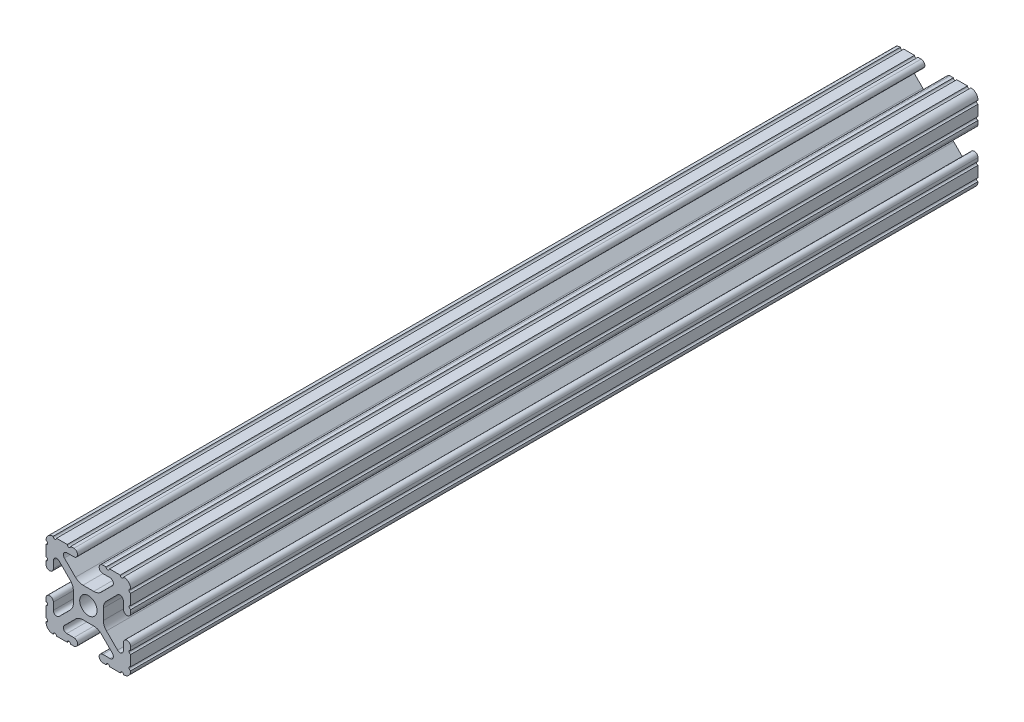
SolidWorks part; units mm, degrees
material "6061 Alloy"
ref_plane "Front Plane" through (0, 0, 0) normal (0, 0, 1) x (1, 0, 0)
ref_plane "Top Plane" through (0, 0, 0) normal (0, 1, 0) x (1, 0, 0)
ref_plane "Right Plane" through (0, 0, 0) normal (1, 0, 0) x (0, 0, -1)
ref_plane "Plane1" through (0, 0, -25.4) normal (0, 0, -1) x (-1, 0, 0)
sketch "Sketch1" plane through (0, 0, -25.4) normal (0, 0, -1) x (-1, 0, 0)
  line L0 (12.7, -9.5504) -> (12.7, -6.3331)
  line L1 (12.7, -5.3171) -> (12.7, -4.3434)
  line L2 (10.4902, -4.3434) -> (10.4902, -6.4748)
  line L3 (8.7558, -7.1932) -> (5.4257, -3.8632)
  line L4 (4.4958, -1.6181) -> (4.4958, 1.6181)
  line L5 (5.4257, 3.8632) -> (8.7558, 7.1932)
  line L6 (10.4902, 6.4748) -> (10.4902, 4.3434)
  line L7 (12.7, 4.3434) -> (12.7, 5.3171)
  line L8 (12.7, 6.3331) -> (12.7, 9.5504)
  line L9 (9.5504, 12.7) -> (6.3331, 12.7)
  line L10 (5.3171, 12.7) -> (4.3434, 12.7)
  line L11 (4.3434, 10.4902) -> (6.4748, 10.4902)
  line L12 (7.1932, 8.7558) -> (3.8632, 5.4257)
  line L13 (1.6181, 4.4958) -> (-1.6181, 4.4958)
  line L14 (-3.8632, 5.4257) -> (-7.1932, 8.7558)
  line L15 (-6.4748, 10.4902) -> (-4.3434, 10.4902)
  line L16 (-4.3434, 12.7) -> (-5.3171, 12.7)
  line L17 (-6.3331, 12.7) -> (-9.5504, 12.7)
  line L18 (-12.7, 9.5504) -> (-12.7, 6.3331)
  line L19 (-12.7, 5.3171) -> (-12.7, 4.3434)
  line L20 (-10.4902, 4.3434) -> (-10.4902, 6.4748)
  line L21 (-8.7558, 7.1932) -> (-5.4257, 3.8632)
  line L22 (-4.4958, 1.6181) -> (-4.4958, -1.6181)
  line L23 (-5.4257, -3.8632) -> (-8.7558, -7.1932)
  line L24 (-10.4902, -6.4748) -> (-10.4902, -4.3434)
  line L25 (-12.7, -4.3434) -> (-12.7, -5.3171)
  line L26 (-12.7, -6.3331) -> (-12.7, -9.5504)
  line L27 (-9.5504, -12.7) -> (-6.3331, -12.7)
  line L28 (-5.3171, -12.7) -> (-4.3434, -12.7)
  line L29 (-4.3434, -10.4902) -> (-6.4748, -10.4902)
  line L30 (-7.1932, -8.7558) -> (-3.8632, -5.4257)
  line L31 (-1.6181, -4.4958) -> (1.6181, -4.4958)
  line L32 (3.8632, -5.4257) -> (7.1932, -8.7558)
  line L33 (6.4748, -10.4902) -> (4.3434, -10.4902)
  line L34 (4.3434, -12.7) -> (5.3171, -12.7)
  line L35 (6.3331, -12.7) -> (9.5504, -12.7)
  arc A0 (12.6998, -10.5664) -> (12.7, -9.5504) centre (12.7, -10.0584) cw
  arc A1 (12.7, -6.3331) -> (12.7, -5.3171) centre (12.7, -5.8251) cw
  arc A2 (12.7, -4.3434) -> (10.4902, -4.3434) centre (11.5951, -4.3434) ccw
  arc A3 (10.4902, -6.4748) -> (8.7558, -7.1932) centre (9.4742, -6.4748) cw
  arc A4 (5.4257, -3.8632) -> (4.4958, -1.6181) centre (7.6708, -1.6181) cw
  arc A5 (4.4958, 1.6181) -> (5.4257, 3.8632) centre (7.6708, 1.6181) cw
  arc A6 (8.7558, 7.1932) -> (10.4902, 6.4748) centre (9.4742, 6.4748) cw
  arc A7 (10.4902, 4.3434) -> (12.7, 4.3434) centre (11.5951, 4.3434) ccw
  arc A8 (12.7, 5.3171) -> (12.7, 6.3331) centre (12.7, 5.8251) cw
  arc A9 (12.7, 9.5504) -> (12.6998, 10.5664) centre (12.7, 10.0584) cw
  arc A10 (12.6998, 10.5664) -> (10.5664, 12.6998) centre (10.5918, 10.5918) ccw
  arc A11 (10.5664, 12.6998) -> (9.5504, 12.7) centre (10.0584, 12.7) cw
  arc A12 (6.3331, 12.7) -> (5.3171, 12.7) centre (5.8251, 12.7) cw
  arc A13 (4.3434, 12.7) -> (4.3434, 10.4902) centre (4.3434, 11.5951) ccw
  arc A14 (6.4748, 10.4902) -> (7.1932, 8.7558) centre (6.4748, 9.4742) cw
  arc A15 (3.8632, 5.4257) -> (1.6181, 4.4958) centre (1.6181, 7.6708) cw
  arc A16 (-1.6181, 4.4958) -> (-3.8632, 5.4257) centre (-1.6181, 7.6708) cw
  arc A17 (-7.1932, 8.7558) -> (-6.4748, 10.4902) centre (-6.4748, 9.4742) cw
  arc A18 (-4.3434, 10.4902) -> (-4.3434, 12.7) centre (-4.3434, 11.5951) ccw
  arc A19 (-5.3171, 12.7) -> (-6.3331, 12.7) centre (-5.8251, 12.7) cw
  arc A20 (-9.5504, 12.7) -> (-10.5664, 12.6998) centre (-10.0584, 12.7) cw
  arc A21 (-10.5664, 12.6998) -> (-12.6998, 10.5664) centre (-10.5918, 10.5918) ccw
  arc A22 (-12.6998, 10.5664) -> (-12.7, 9.5504) centre (-12.7, 10.0584) cw
  arc A23 (-12.7, 6.3331) -> (-12.7, 5.3171) centre (-12.7, 5.8251) cw
  arc A24 (-12.7, 4.3434) -> (-10.4902, 4.3434) centre (-11.5951, 4.3434) ccw
  arc A25 (-10.4902, 6.4748) -> (-8.7558, 7.1932) centre (-9.4742, 6.4748) cw
  arc A26 (-5.4257, 3.8632) -> (-4.4958, 1.6181) centre (-7.6708, 1.6181) cw
  arc A27 (-4.4958, -1.6181) -> (-5.4257, -3.8632) centre (-7.6708, -1.6181) cw
  arc A28 (-8.7558, -7.1932) -> (-10.4902, -6.4748) centre (-9.4742, -6.4748) cw
  arc A29 (-10.4902, -4.3434) -> (-12.7, -4.3434) centre (-11.5951, -4.3434) ccw
  arc A30 (-12.7, -5.3171) -> (-12.7, -6.3331) centre (-12.7, -5.8251) cw
  arc A31 (-12.7, -9.5504) -> (-12.6998, -10.5664) centre (-12.7, -10.0584) cw
  arc A32 (-12.6998, -10.5664) -> (-10.5664, -12.6998) centre (-10.5918, -10.5918) ccw
  arc A33 (-10.5664, -12.6998) -> (-9.5504, -12.7) centre (-10.0584, -12.7) cw
  arc A34 (-6.3331, -12.7) -> (-5.3171, -12.7) centre (-5.8251, -12.7) cw
  arc A35 (-4.3434, -12.7) -> (-4.3434, -10.4902) centre (-4.3434, -11.5951) ccw
  arc A36 (-6.4748, -10.4902) -> (-7.1932, -8.7558) centre (-6.4748, -9.4742) cw
  arc A37 (-3.8632, -5.4257) -> (-1.6181, -4.4958) centre (-1.6181, -7.6708) cw
  arc A38 (1.6181, -4.4958) -> (3.8632, -5.4257) centre (1.6181, -7.6708) cw
  arc A39 (7.1932, -8.7558) -> (6.4748, -10.4902) centre (6.4748, -9.4742) cw
  arc A40 (4.3434, -10.4902) -> (4.3434, -12.7) centre (4.3434, -11.5951) ccw
  arc A41 (5.3171, -12.7) -> (6.3331, -12.7) centre (5.8251, -12.7) cw
  arc A42 (9.5504, -12.7) -> (10.5664, -12.6998) centre (10.0584, -12.7) cw
  arc A43 (10.5664, -12.6998) -> (12.6998, -10.5664) centre (10.5918, -10.5918) ccw
  circle A44 centre (0, 0) radius 2.6035
extrude "Boss-Extrude1" add sketch "Sketch1" against normal blind 254
